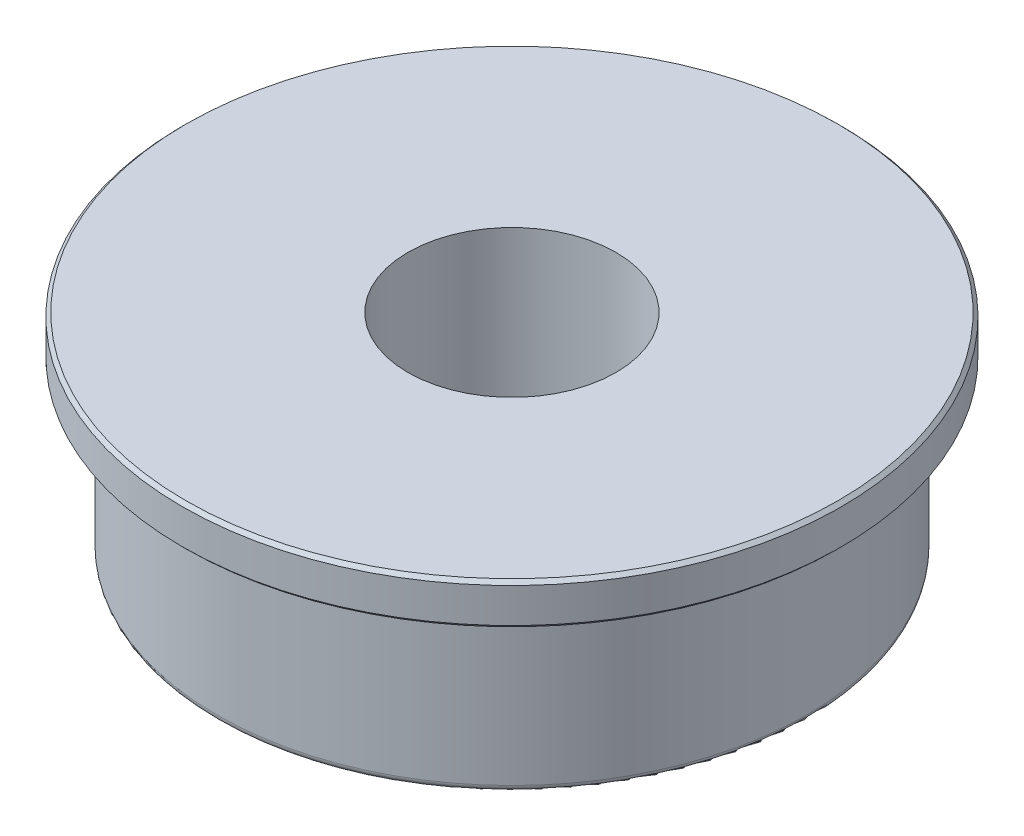
SolidWorks part; units mm, degrees
material "不锈钢 (铁素体)"
ref_plane "前视基准面" through (0, 0, 0) normal (0, 0, 1) x (1, 0, 0)
ref_plane "上视基准面" through (0, 0, 0) normal (0, 1, 0) x (1, 0, 0)
ref_plane "右视基准面" through (0, 0, 0) normal (1, 0, 0) x (0, 0, -1)
sketch "草图1" plane through (0, 0, 0) normal (0, 1, 0) x (1, 0, 0)
  circle A0 centre (0, 0) radius 8.5
  circle A1 centre (0, 0) radius 3
  dimension "D1" = 17
  dimension "D2" = 6
extrude "凸台-拉伸1" add sketch "草图1" along normal blind 6
sketch "草图2" plane through (0, 6, 0) normal (0, 1, 0) x (1, 0, 0)
  circle A0 centre (0, 0) radius 9.5
  circle A1 centre (0, 0) radius 3
  dimension "D1" = 19
  dimension "D2" = 6
extrude "凸台-拉伸2" add sketch "草图2" against normal blind 1.2
fillet "圆角1" radius 0.2 1 edges at (0, 0, 8.5)
chamfer "倒角1" distance 0.1 angle 45 2 edges at (0, 4.8, 9.5) (0, 6, 9.5)
